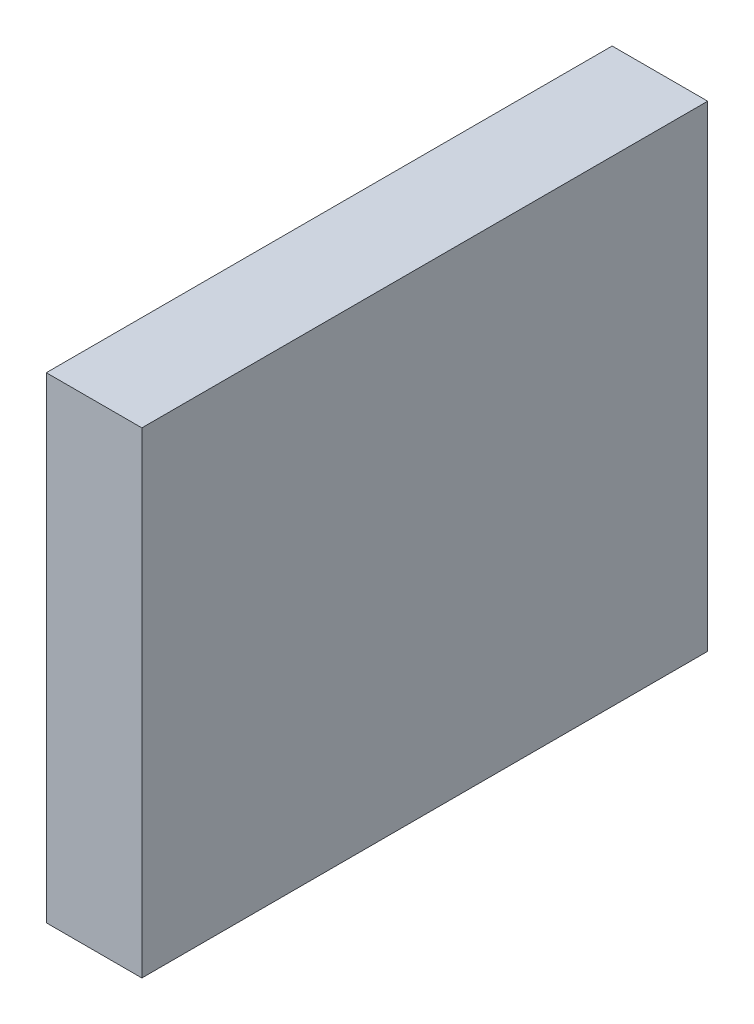
SolidWorks part; units mm, degrees
ref_plane "Front Plane" through (0, 0, 0) normal (1, 0, 0) x (0, 1, 0)
ref_plane "Top Plane" through (0, 0, 0) normal (0, 0, 1) x (0, 1, 0)
ref_plane "Right Plane" through (0, 0, 0) normal (0, 1, 0) x (-1, 0, 0)
sketch "Sketch1" plane through (0, 0, 0) normal (1, 0, 0) x (0, 1, 0)
  line L1 (8.9, -10.57) -> (-8.9, -10.57)
  line L2 (8.9, -10.57) -> (8.9, 10.57)
  line L3 (8.9, 10.57) -> (-8.9, 10.57)
  line L4 (-8.9, -10.57) -> (-8.9, 10.57)
  line L5 (8.9, -10.57) -> (-8.9, 10.57) construction
  line L6 (8.9, 10.57) -> (-8.9, -10.57) construction
  point P0 (0, 0)
  dimension "D1" = 21.14
  dimension "D2" = 17.8
extrude "Boss-Extrude1" add sketch "Sketch1" along normal blind 3.57 contours L4 L3 L2 L1
